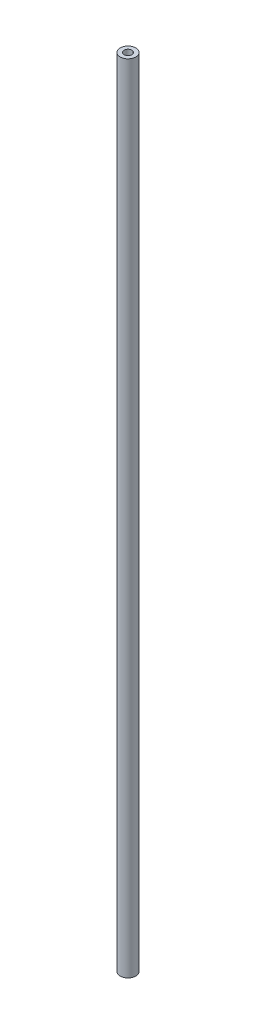
SolidWorks part; units mm, degrees
material "Thornel VCB-20 碳布"
ref_plane "前视基准面" through (0, 0, 0) normal (0, 0, 1) x (1, 0, 0)
ref_plane "上视基准面" through (0, 0, 0) normal (0, 1, 0) x (1, 0, 0)
ref_plane "右视基准面" through (0, 0, 0) normal (1, 0, 0) x (0, 0, -1)
other "Configuration Table"
sketch "草图1" plane through (0, 0, 0) normal (0, 1, 0) x (1, 0, 0)
  circle A0 centre (0, 0) radius 3
  circle A1 centre (0, 0) radius 1.5
  dimension "D1" = 6
  dimension "D2" = 3
extrude "凸台-拉伸1" add sketch "草图1" along normal blind 303.8
